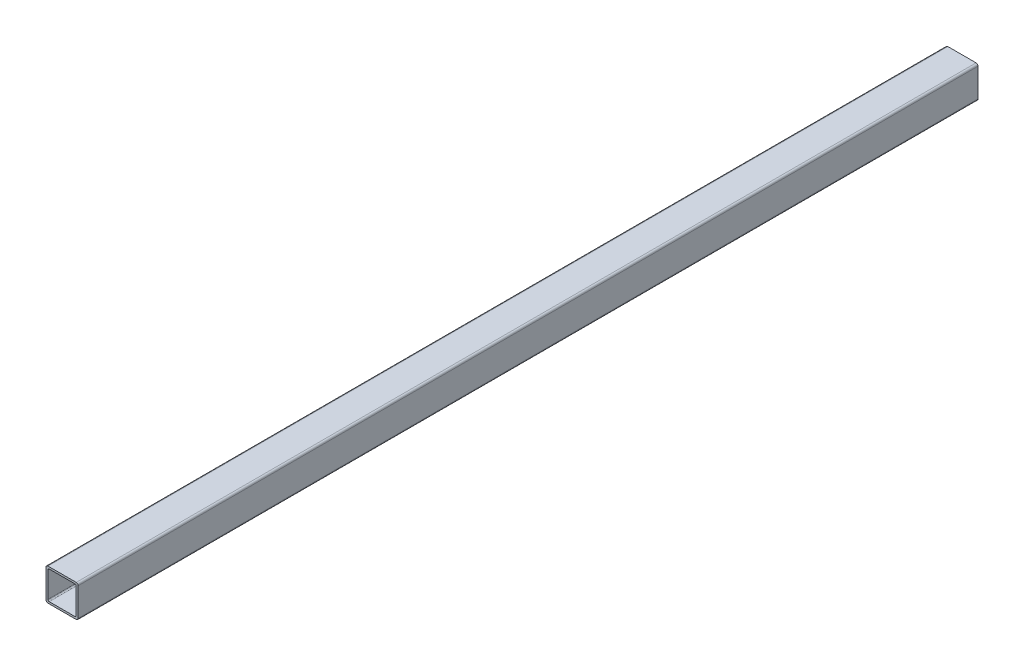
SolidWorks part; units mm, degrees
material "AISI 1020"
ref_plane "Спереди" through (0, 0, 0) normal (0, 0, 1) x (1, 0, 0)
ref_plane "Сверху" through (0, 0, 0) normal (0, 1, 0) x (1, 0, 0)
ref_plane "Справа" through (0, 0, 0) normal (1, 0, 0) x (0, 0, -1)
sketch "Эскиз2" plane through (0, 0, 0) normal (0, 0, 1) x (1, 0, 0)
  line B0 (6, 100) -> (94, 100)
  line B1 (0, 94) -> (0, 6)
  line B2 (6, 0) -> (94, 0)
  line B3 (100, 94) -> (100, 6)
  line B4 (10, 94) -> (90, 94)
  line B5 (6, 90) -> (6, 10)
  line B6 (10, 6) -> (90, 6)
  line B7 (94, 90) -> (94, 10)
  arc B8 (0, 6) -> (6, 0) centre (6, 6) ccw
  arc B9 (94, 0) -> (100, 6) centre (94, 6) ccw
  arc B10 (94, 100) -> (100, 94) centre (94, 94) cw
  arc B11 (6, 100) -> (0, 94) centre (6, 94) ccw
  arc B12 (6, 10) -> (10, 6) centre (10, 10) ccw
  arc B13 (90, 6) -> (94, 10) centre (90, 10) ccw
  arc B14 (90, 94) -> (94, 90) centre (90, 90) cw
  arc B15 (10, 94) -> (6, 90) centre (10, 90) ccw
sketch_block_instance "Пр_тр_100х100х6-1"
sketch_block "Пр_тр_100х100х6" parameters "D3"=6, "D4"=4, "D1"=100, "D2"=6
extrude "Бобышка-Вытянуть1" add sketch "Эскиз2" along normal up to surface (2800 mm away)
